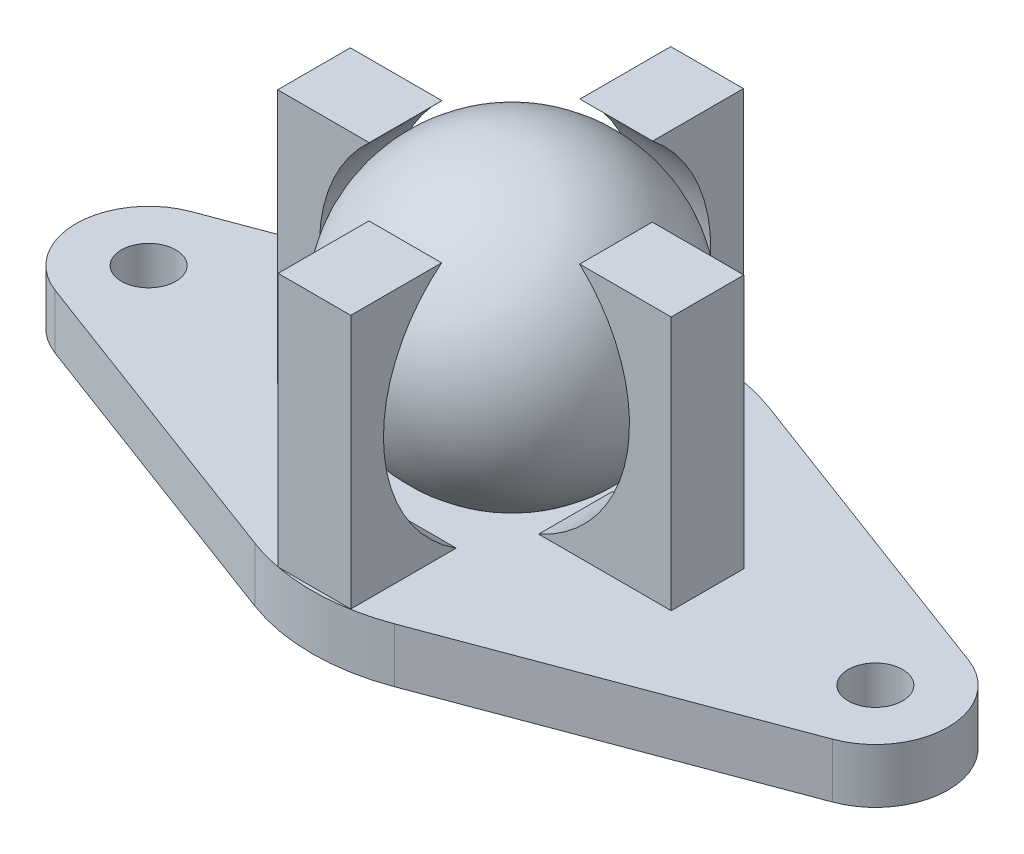
SolidWorks part; units mm, degrees
ref_plane "Alzado" through (0, 0, 0) normal (0, 0, 1) x (1, 0, 0)
ref_plane "Planta" through (0, 0, 0) normal (0, 1, 0) x (1, 0, 0)
ref_plane "Vista lateral" through (0, 0, 0) normal (1, 0, 0) x (0, 0, -1)
sketch "Croquis1" plane through (0, 0, 0) normal (0, 1, 0) x (1, 0, 0)
  line L0 (0, -23.9386) -> (0, -11) construction
  line L1 (3.85, 10.3042) -> (21.4, 3.747)
  line L2 (3.85, -10.3042) -> (21.4, -3.747)
  line L3 (-3.85, -10.3042) -> (-21.4, -3.747)
  line L4 (-3.85, 10.3042) -> (-21.4, 3.747)
  line L5 (0, 11) -> (0, 31.4497) construction
  circle A0 centre (20, 0) radius 1.5
  arc A1 (3.85, 10.3042) -> (-3.85, 10.3042) centre (0, 0) ccw
  arc A2 (21.4, -3.747) -> (21.4, 3.747) centre (20, 0) ccw
  circle A3 centre (-20, 0) radius 1.5
  arc A4 (-21.4, -3.747) -> (-21.4, 3.747) centre (-20, 0) cw
  arc A5 (-3.85, -10.3042) -> (3.85, -10.3042) centre (0, 0) ccw
  dimension "D2" = 3
  dimension "D3" = 22
  dimension "D4" = 8
  dimension "D1" = 20
extrude "Saliente-Extruir1" add sketch "Croquis1" along normal blind 3
sketch "Croquis2" plane through (0, 3, 0) normal (0, 1, 0) x (1, 0, 0)
  line L0 (0, -11) -> (0, 11) construction
  line L1 (3.171, 1.9323) -> (3.171, -1.9323)
  line L2 (-1.9323, 3.171) -> (1.9323, 3.171)
  line L3 (-1.9323, 3.171) -> (-1.9323, 10.829)
  line L4 (-1.9323, 10.829) -> (1.9323, 10.829)
  line L5 (1.9323, 3.171) -> (1.9323, 10.829)
  line L6 (-1.9323, 3.171) -> (1.9323, 10.829) construction
  line L7 (-1.9323, 10.829) -> (1.9323, 3.171) construction
  line L8 (-1.9323, -3.171) -> (1.9323, -3.171)
  line L9 (-1.9323, -3.171) -> (-1.9323, -10.829)
  line L10 (-1.9323, -10.829) -> (1.9323, -10.829)
  line L11 (1.9323, -3.171) -> (1.9323, -10.829)
  line L12 (-1.9323, -3.171) -> (1.9323, -10.829) construction
  line L13 (-1.9323, -10.829) -> (1.9323, -3.171) construction
  line L14 (3.171, 1.9323) -> (10.829, 1.9323)
  line L15 (10.829, 1.9323) -> (10.829, -1.9323)
  line L16 (3.171, -1.9323) -> (10.829, -1.9323)
  line L17 (3.171, 1.9323) -> (10.829, -1.9323) construction
  line L18 (10.829, 1.9323) -> (3.171, -1.9323) construction
  line L19 (1.9323, -3.171) -> (-1.9323, -3.171)
  line L20 (1.9323, -3.171) -> (1.9323, -10.829)
  line L21 (1.9323, -10.829) -> (-1.9323, -10.829)
  line L22 (-1.9323, -3.171) -> (-1.9323, -10.829)
  line L23 (1.9323, -3.171) -> (-1.9323, -10.829) construction
  line L24 (1.9323, -10.829) -> (-1.9323, -3.171) construction
  line L25 (-3.171, -1.9323) -> (-3.171, 1.9323)
  line L26 (-3.171, -1.9323) -> (-10.829, -1.9323)
  line L27 (-10.829, -1.9323) -> (-10.829, 1.9323)
  line L28 (-3.171, 1.9323) -> (-10.829, 1.9323)
  line L29 (-3.171, -1.9323) -> (-10.829, 1.9323) construction
  line L30 (-10.829, -1.9323) -> (-3.171, 1.9323) construction
  arc A0 (-3.85, -10.3042) -> (3.85, -10.3042) centre (0, 0) ccw construction
  arc A1 (3.85, 10.3042) -> (-3.85, 10.3042) centre (0, 0) ccw construction
  circle A2 centre (0, 0) radius 7
  point P11 (0, 7)
  point P16 (0, -7)
  point P24 (7, 0)
  point P29 (0, -7)
  point P34 (-7, 0)
  point P39 (0, 0)
  dimension "D1" = 14
  dimension "D2" = 4
sketch3d "Croquis3D1"
  line L0 (1.9323, 3, -10.8069) -> (1.9323, 17, -10.8069)
  line L2 (1.9323, 3, 10.8069) -> (1.9323, 3, 5.0011)
  line L3 (1.9323, 17, 10.8069) -> (1.9323, 17, 5.8069)
  line L4 (1.9323, 17, -10.8069) -> (1.9323, 17, -5.8069)
  line L5 (1.9323, 3, -10.8069) -> (1.9323, 3, -5.0011)
  line L6 (1.9323, 3, -3.171) -> (1.9323, 3, -10.829) construction
  line L7 (1.9323, 3, 10.8069) -> (1.9323, 17, 10.8069)
  arc A0 (1.9323, 3, -5.0011) -> (1.9323, 17, -5.8069) centre (1.9323, 10.2896, -0.3717) ccw
  arc A1 (1.9323, 17, 5.8069) -> (1.9323, 3, 5.0011) centre (1.9323, 10.2896, 0.3717) cw
  point P0 (0, 0, 0)
  point P10 (10.5677, 10.2896, -0.3717)
  point P14 (10.5677, 10.2896, 0.3717)
  dimension "D1" = 5
  dimension "D2" = 14
extrude "Saliente-Extruir2" add sketch "Croquis3D1" along direction (1, 0, 0) on the side of the normal blind 4
sketch "Croquis3" plane through (0, 0, 0) normal (0, 0, 1) x (1, 0, 0)
  line L0 (0, 3) -> (0, 19)
  line L1 (-1.9323, 3) -> (1.9323, 3) construction
  arc A0 (0, 19) -> (0, 3) centre (0, 11) ccw
  dimension "D1" = 16
revolve "Revolución1" add sketch "Croquis3" angle 360 about L0
sketch3d "Croquis3D2"
  line L1 (10.829, 3, -1.9323) -> (10.829, 17, -1.9323)
  line L4 (-10.829, 3, -1.9323) -> (-3.5319, 3, -1.9323)
  line L6 (10.829, 17, -1.9323) -> (5.7892, 17, -1.9323)
  line L8 (-10.829, 17, -1.9323) -> (-5.7892, 17, -1.9323)
  line L9 (10.829, 3, -1.9323) -> (3.5319, 3, -1.9323)
  line L10 (-10.829, 3, -1.9323) -> (-10.829, 17, -1.9323)
  arc A0 (3.5319, 3, -1.9323) -> (5.7892, 17, -1.9323) centre (0.0323, 10.7463, -1.9323) ccw
  arc A1 (-5.7892, 17, -1.9323) -> (-3.5319, 3, -1.9323) centre (-0.0323, 10.7463, -1.9323) cw
  point P8 (0.0323, 10.7463, 6.5678)
  point P9 (0, 0, 0)
  point P10 (0, 0, 0)
  point P13 (-0.0323, 10.7463, 6.5678)
  dimension "D2" = 17.0001
  dimension "D1" = 14
extrude "Saliente-Extruir3" add sketch "Croquis3D2" along direction (0, 0, 1) on the side against the normal blind 4
